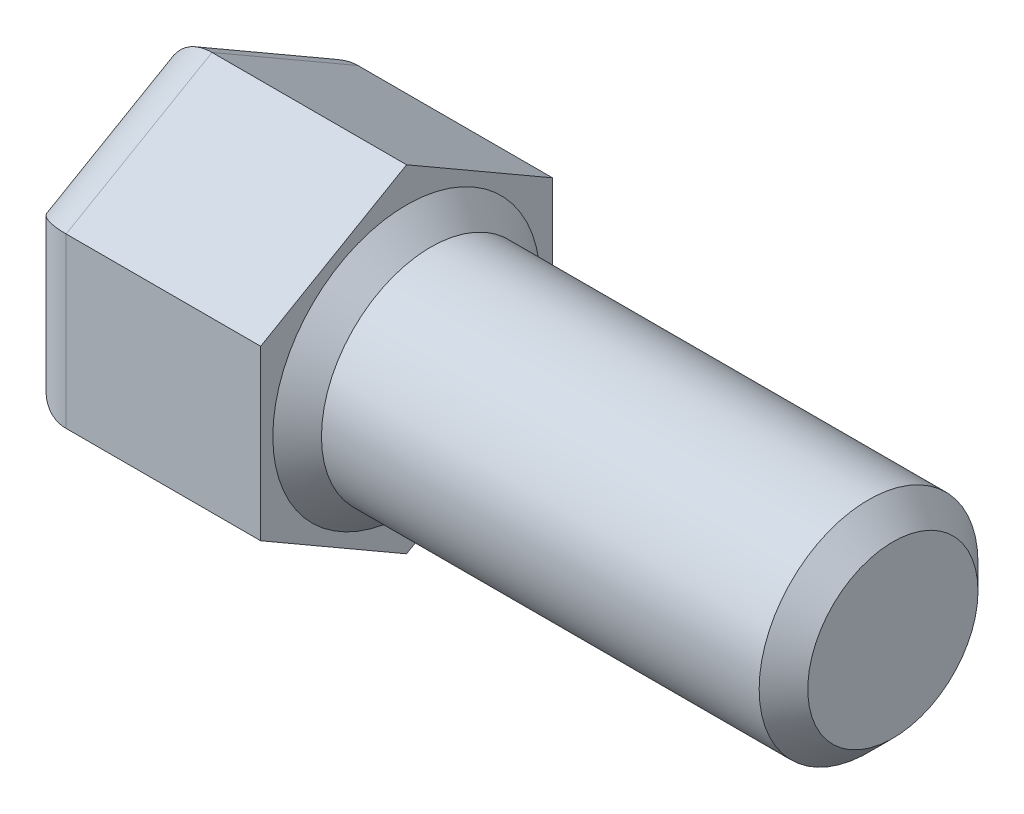
SolidWorks part; units mm, degrees
ref_plane "前基準面" through (0, 0, 0) normal (0, 0, 1) x (1, 0, 0)
ref_plane "上基準面" through (0, 0, 0) normal (0, 1, 0) x (1, 0, 0)
ref_plane "右基準面" through (0, 0, 0) normal (1, 0, 0) x (0, 0, -1)
ref_plane "平面1"
sketch "草圖1" plane through (0, 0, 0) normal (1, 0, 0) x (0, 1, 0)
  line L0 (6.9282, 0) -> (3.4641, -6)
  line L1 (3.4641, -6) -> (-3.4641, -6)
  line L2 (-3.4641, -6) -> (-6.9282, 0)
  line L3 (-6.9282, 0) -> (-3.4641, 6)
  line L4 (-3.4641, 6) -> (3.4641, 6)
  line L5 (3.4641, 6) -> (6.9282, 0)
  dimension "D1" = 12
extrude "擠出1" add sketch "草圖1" along normal blind 10
sketch "草圖2" plane through (10, 0, 0) normal (1, 0, 0) x (0, 0, -1)
  circle A0 centre (0, 0) radius 4.5
  dimension "D1" = 9
extrude "擠出2" add sketch "草圖2" along normal blind 20
fillet "圓角1" radius 2 6 edges at (0, -5.1962, 3) (0, -5.1962, -3) (0, 0, -6) (0, 5.1962, -3) (0, 5.1962, 3) (0, 0, 6)
chamfer "倒角1" distance 1 distance2 1 2 edges at (10, 0, -4.5) (30, 0, -4.5)
